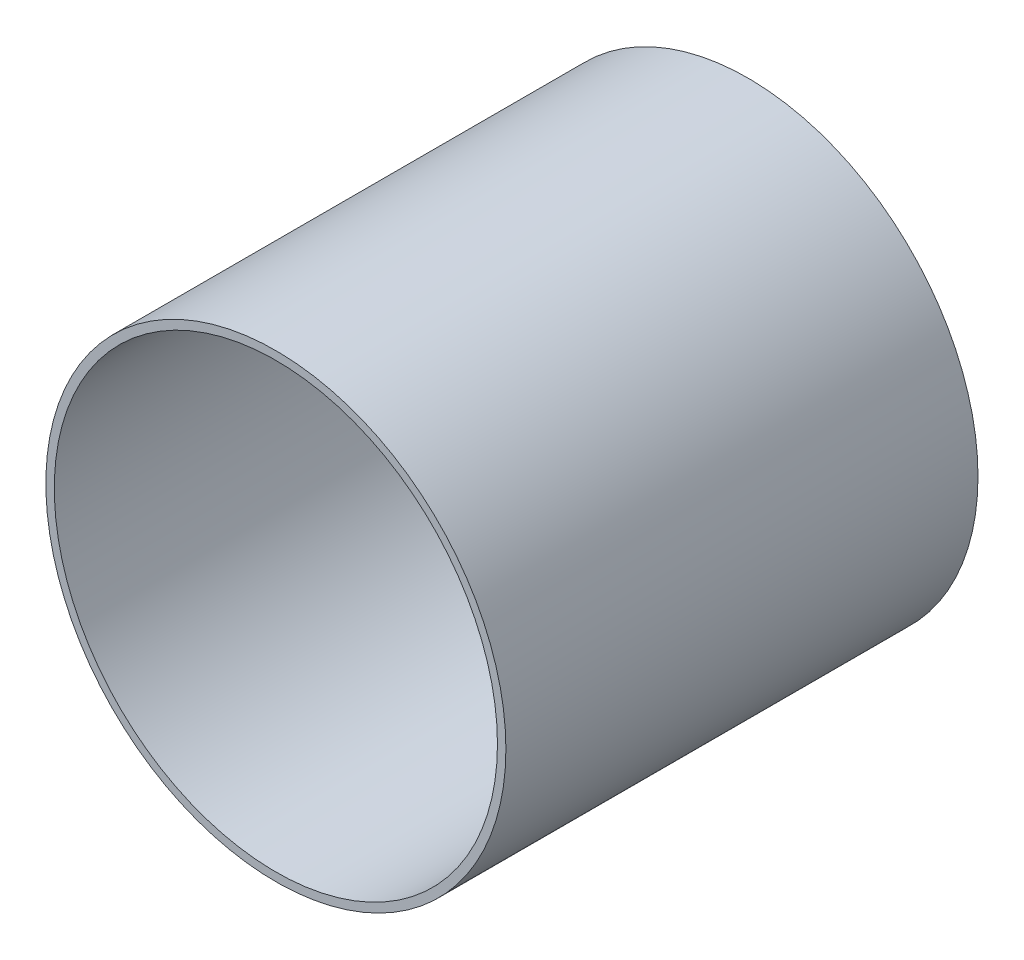
SolidWorks part; units mm, degrees
material "Wound G12 Fiberglass"
ref_plane "Front Plane" through (0, 0, 0) normal (0, 0, 1) x (1, 0, 0)
ref_plane "Top Plane" through (0, 0, 0) normal (0, 1, 0) x (1, 0, 0)
ref_plane "Right Plane" through (0, 0, 0) normal (1, 0, 0) x (0, 0, -1)
sketch "Sketch1" plane through (0, 0, 0) normal (0, 0, 1) x (1, 0, 0)
  circle A0 centre (0, 0) radius 47.6885
  circle A1 centre (0, 0) radius 49.5046
  dimension "D1" = 99.0092
  dimension "D2" = 95.377
extrude "Boss-Extrude1" add sketch "Sketch1" along normal blind 101.6
